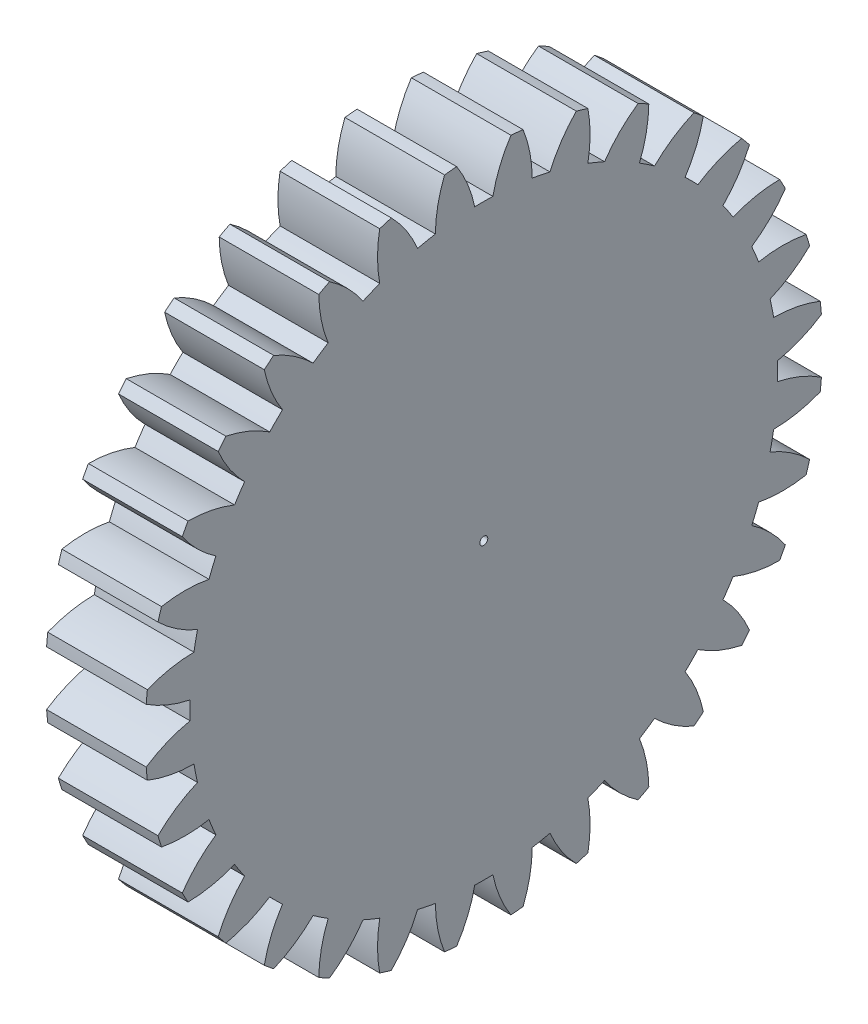
SolidWorks part; units mm, degrees
ref_plane "Plane1" through (0, 0, 0) normal (0, 0, 1) x (1, 0, 0)
ref_plane "Plane2" through (0, 0, 0) normal (0, 1, 0) x (1, 0, 0)
ref_plane "Plane3" through (0, 0, 0) normal (1, 0, 0) x (0, 0, -1)
sketch "HoldingSke" plane through (0, 0, 0) normal (0, 1, 0) x (1, 0, 0)
  line L0 (0, 0) -> (0.424, -0.265)
  line L1 (-15, 0) -> (100, 0) construction
  line L2 (0, 0) -> (-2.1039, 2.3779)
  line L3 (0, 0) -> (-11.863, 4.5341)
  line L4 (0, 0) -> (7.3237, 4.5764)
  line L5 (0, 0) -> (-46.8476, -17.4728)
  line L6 (0, 0) -> (-8.2896, -5.593)
  line L7 (-2.1039, 2.3779) -> (8.6586, 51.2059)
  line L8 (-76.2, 54.61) -> (-76.1, 54.61)
  line L9 (-71.009, 38.7566) -> (-53.1078, 45.2721)
  line L10 (-76.2, 71.12) -> (104.1128, 71.12)
  line L11 (0, 0) -> (-10, 0)
  line L12 (-76.2, 101.6) -> (-76.133, 101.6)
  line L13 (24.9733, 27.94) -> (52.9518, 28.4284)
  line L14 (24.9733, 27.94) -> (24.9743, 27.94)
  line L15 (24.9733, 27.94) -> (100.4006, 29.5858)
  line L16 (-63.627, -2) -> (-12.827, -2)
  circle A0 centre (0, 0) radius 0.4
  circle A1 centre (0, 0) radius 29.499
  circle A2 centre (0, 0) radius 37.5
  circle A3 centre (0, 0) radius 0.4
  dimension "MHD" = 58.998
  dimension "Hub_dia" = 75
  dimension "Bore" = 0.8
  dimension "MBD" = 0.8
  dimension "Num_teeth" = 32
  dimension "Pitch" = 0.5
  dimension "Overall_len" = 50
  dimension "Show_teeth" = 32
  dimension "Thickness" = 10
  dimension "OAL" = 50.0001
  dimension "T_dim" = 0.1
  dimension "Ap" = 20
  dimension "H" = 19.05
  dimension "Pitch_radius" = 180.3128
  dimension "Width" = 10
  dimension "Backlash" = 0.067
  dimension "Addendum_fac" = 1
  dimension "Dedendum_fac" = 1.25
  dimension "Clearance_fac" = 0.25
  dimension "Dedendum_add" = 0.001
  dimension "Module" = 2
sketch "BasProSke" plane through (0, 0, 0) normal (0, 1, 0) x (1, 0, 0)
  line L0 (-10, 0) -> (60, 0) construction
  line L1 (0, 0) -> (0, 34)
  line L2 (0, 0) -> (10, 0)
  line L3 (10, 0) -> (10, 34)
  line L4 (10, 34) -> (0, 34)
  dimension "Thickness" = 10
  dimension "Diameter" = 68
revolve "Base-Revolve" add sketch "BasProSke" angle 360 about L0
sketch "TooCutSke" plane through (0, 0, 0) normal (1, 0, 0) x (0, 0, -1)
  line L1 (0, 0) -> (0, 107) construction
  line L2 (0, 0) -> (-1.6874, 31.9555) construction
  line L3 (0, 0) -> (-6.2666, 63.6261) construction
  line L4 (-1.6874, 31.9555) -> (-3.1333, 31.8131) construction
  arc A0 (0.9098, 29.485) -> (-0.9098, 29.485) centre (0, 0) ccw
  arc A1 (2.7408, 33.9148) -> (-2.7408, 33.9148) centre (0, 0) ccw
  circle A2 centre (0, 0) radius 32 construction
  circle A3 centre (0, 0) radius 30.0702 construction
  arc A4 (-0.9098, 29.485) -> (-2.7408, 33.9148) centre (-13.4454, 26.8968) ccw
  arc A5 (2.7408, 33.9148) -> (0.9098, 29.485) centre (13.4454, 26.8968) ccw
  dimension "Root_dia" = 58.998
  dimension "Overcut_dia" = 68.0508
  dimension "Pitch_dia" = 64
  dimension "Base_dia" = 60.1403
  dimension "Flank_rad" = 12.8
  dimension "Half_ang" = 5.625
  dimension "Half_CT" = 1.4529
extrude "ToothCut" cut sketch "TooCutSke" along normal through all
fillet "Breaks" [suppressed] radius 0.04
fillet "RootFillets" [suppressed] radius 0.501
pattern_circular "TeethCuts" count 32 every 11.25 about axis through (-10, 0, 0) along (1, 0, 0) of "ToothCut", "RootFillets", "Breaks"
sketch "HubNeaOneSke" plane through (0, 0, 0) normal (-1, 0, 0) x (0, 0, 1)
  circle A0 centre (0, 0) radius 29.499
  dimension "Diameter" = 58.998
extrude "HubNearOne" [suppressed] add sketch "HubNeaOneSke" along normal blind 40.0001
sketch "HubNeaBotSke" plane through (0, 0, 0) normal (-1, 0, 0) x (0, 0, 1)
  circle A0 centre (0, 0) radius 29.499
  dimension "Diameter" = 58.998
extrude "HubNearBoth" [suppressed] add sketch "HubNeaBotSke" along normal blind 20
ref_plane "FarPln" through (10, 0, 0) normal (1, 0, 0) x (0, 0, -1)
sketch "HubFarSke" plane through (10, 0, 0) normal (1, 0, 0) x (0, 0, -1)
  circle A0 centre (0, 0) radius 29.499
  dimension "Diameter" = 58.998
extrude "HubFar" [suppressed] add sketch "HubFarSke" along normal blind 20
sketch "BorSke" plane through (0, 0, 0) normal (1, 0, 0) x (0, 0, -1)
  circle A0 centre (0, 0) radius 0.4
  dimension "Diameter" = 0.8
extrude "Bore" cut sketch "BorSke" along normal mid plane 100.0001
sketch "KeySke" plane through (0, 0, 0) normal (1, 0, 0) x (0, 0, -1)
  line L0 (-0.05, 0) -> (-0.05, 0.5)
  line L1 (-0.05, 0.5) -> (0.05, 0.5)
  line L2 (0.05, 0.5) -> (0.05, 0)
  line L3 (0, 0) -> (0, 34) construction
  line L4 (-0.05, 0) -> (0.05, 0)
  dimension "Offset" = 0.5
  dimension "Width" = 0.1
extrude "Keyway" [suppressed] cut sketch "KeySke" along normal mid plane 100.0001
pattern_circular "Keyway2" [suppressed] count 2 every 90 about axis through (-10, 0, 0) along (1, 0, 0)
equation "' \"Module@HoldingSke\" = 6.35"
equation "' \"Num_teeth@HoldingSke\" = 12"
equation "' \"Ap@HoldingSke\" =  20"
equation "' \"Ap@HoldingSke\" = 20"
equation "' \"Width@HoldingSke\" = 0.5 * 25.4"
equation "' \"Hub_dia@HoldingSke\"= 1 * 25.4"
equation "' \"Hub_dia@HoldingSke\" = 1 * 25.4"
equation "' \"Overall_len@HoldingSke\" = 1.0 * 25.4"
equation "' \"Bore@HoldingSke\" = 0.75 * 25.4"
equation "' \"T_dim@HoldingSke\" = 0.1 * 25.4"
equation "' \"Width@KeySke\" = 0.25 * 25.4"
equation "' \"Show_teeth@HoldingSke\" = 13"
equation "' \"Backlash@HoldingSke\" = 0.009 * 25.4"
equation "' \"Addendum_fac@HoldingSke\" = 1.0"
equation "' \"Dedendum_fac@HoldingSke\" = 1.25"
equation "' \"Dedendum_add@HoldingSke\" = 0.00005 * 25.4"
equation "' \"Clearance_fac@HoldingSke\" = 0.25"
equation "\"Pitch@HoldingSke\" = 1 / \"Module@HoldingSke\""
equation "\"Overcut_dia@TooCutSke\" = (\"Num_teeth@HoldingSke\" + 2 * \"Addendum_fac@HoldingSke\") / \"Pitch@HoldingSke\" + 0.002 * 25.4"
equation "\"Pitch_dia@TooCutSke\" = \"Num_teeth@HoldingSke\" / \"Pitch@HoldingSke\""
equation "\"Base_dia@TooCutSke\" = \"Num_teeth@HoldingSke\" / \"Pitch@HoldingSke\" * cos((\"Ap@HoldingSke\"  * 3.14159265 / 180))"
equation "\"Root_dia@TooCutSke\" = (\"Num_teeth@HoldingSke\" + 2) / \"Pitch@HoldingSke\" - 2 * (\"Addendum_fac@HoldingSke\" + \"Dedendum_fac@HoldingSke\") / \"Pitch@HoldingSke\" - \"Dedendum_add@HoldingSke\" * 2"
equation "\"Half_ang@TooCutSke\" = 180 / \"Num_teeth@HoldingSke\""
equation "\"Half_CT@TooCutSke\" = \"Num_teeth@HoldingSke\" / \"Pitch@HoldingSke\" * sin((3.14159265 / 2 / \"Num_teeth@HoldingSke\")) / 2 - 7 * \"Backlash@HoldingSke\" / 4"
equation "\"Flank_rad@TooCutSke\" = \"Num_teeth@HoldingSke\" / \"Pitch@HoldingSke\" / 5"
equation "\"Radius@RootFillets\" = \"Clearance_fac@HoldingSke\" / \"Pitch@HoldingSke\" + \"Dedendum_add@HoldingSke\""
equation "\"Break_rad@Breaks\" = 0.02 / \"Pitch@HoldingSke\""
equation "\"Thickness@HoldingSke\" = \"Width@HoldingSke\""
equation "\"OAL@HoldingSke\" = \"Thickness@HoldingSke\""
equation "\"MHD@HoldingSke\" = (\"Num_teeth@HoldingSke\" + 2) / \"Pitch@HoldingSke\" - 2 * (\"Addendum_fac@HoldingSke\" + \"Dedendum_fac@HoldingSke\")  / \"Pitch@HoldingSke\" - \"Dedendum_add@HoldingSke\" * 2"
equation "\"MBD@HoldingSke\" = (\"Num_teeth@HoldingSke\" + 2) / \"Pitch@HoldingSke\" - 2 * (\"Addendum_fac@HoldingSke\" + \"Dedendum_fac@HoldingSke\")  / \"Pitch@HoldingSke\" - \"Dedendum_add@HoldingSke\" * 2 - 0.002 * 25.4"
equation "\"MHD@HoldingSke\" = ((sgn( \"MHD@HoldingSke\" - \"Hub_dia@HoldingSke\" )-1)*( \"MHD@HoldingSke\" - \"Hub_dia@HoldingSke\" ))/-2+ \"Hub_dia@HoldingSke\""
equation "\"MBD@HoldingSke\" = ((sgn( \"MBD@HoldingSke\" - \"Bore@HoldingSke\" )-1)*( \"MBD@HoldingSke\" - \"Bore@HoldingSke\" ))/-2+ \"Bore@HoldingSke\""
equation "\"OAL@HoldingSke\" = ((sgn( \"OAL@HoldingSke\" - \"Overall_len@HoldingSke\" )+1)*( \"OAL@HoldingSke\" - \"Overall_len@HoldingSke\" ))/2 + \"Overall_len@HoldingSke\" + 0.000002 * 25.4"
equation "\"Num_teeth@TeethCuts\" = int( \"Show_teeth@HoldingSke\" ) + 1"
equation "\"Num_teeth@TeethCuts\" = ((sgn( \"Num_teeth@TeethCuts\" - \"Num_teeth@HoldingSke\" )-1)*( \"Num_teeth@TeethCuts\" - \"Num_teeth@HoldingSke\" ))/-2+ \"Num_teeth@HoldingSke\""
equation "\"Num_teeth@TeethCuts\" = ((sgn( \"Num_teeth@TeethCuts\" - 2.0)+1)*( \"Num_teeth@TeethCuts\" - 2.0))/2 +2.0"
equation "\"Angle@TeethCuts\" = 360.0 / \"Num_teeth@HoldingSke\""
equation "\"Diameter@BasProSke\" = (\"Num_teeth@HoldingSke\" + 2 * \"Addendum_fac@HoldingSke\") / \"Pitch@HoldingSke\""
equation "\"Thickness@BasProSke\"  = \"Thickness@HoldingSke\""
equation "' \"Fillet_rad@BasProSke\" =  \"Thickness@HoldingSke\" * 0.05"
equation "' \"Fillet_rad@BasProSke\" = \"Thickness@HoldingSke\" * 0.05"
equation "\"MHD@HoldingSke\" = ((sgn( \"MHD@HoldingSke\" - \"Root_dia@TooCutSke\" )-1)*( \"MHD@HoldingSke\" - \"Root_dia@TooCutSke\" ))/-2+ \"Root_dia@TooCutSke\""
equation "\"Diameter@HubNeaOneSke\" = \"MHD@HoldingSke\""
equation "\"Length@HubNearOne\" = \"OAL@HoldingSke\" - \"Thickness@BasProSke\""
equation "\"Diameter@HubNeaBotSke\" = \"MHD@HoldingSke\""
equation "\"Length@HubNearBoth\" = ( \"OAL@HoldingSke\" - \"Thickness@BasProSke\" ) / 2.0"
equation "\"Thickness@FarPln\" = \"Thickness@BasProSke\""
equation "\"Diameter@HubFarSke\" = \"MHD@HoldingSke\""
equation "\"Length@HubFar\" = ( \"OAL@HoldingSke\" - \"Thickness@BasProSke\" ) / 2.0"
equation "\"Diameter@BorSke\" = \"MBD@HoldingSke\""
equation "\"D1@Bore\" = \"OAL@HoldingSke\" * 2.0"
equation "\"D1@Keyway\" = \"OAL@HoldingSke\" * 2.0"
equation "\"Offset@KeySke\" = \"T_dim@HoldingSke\" + \"MBD@HoldingSke\" / 2.0"
